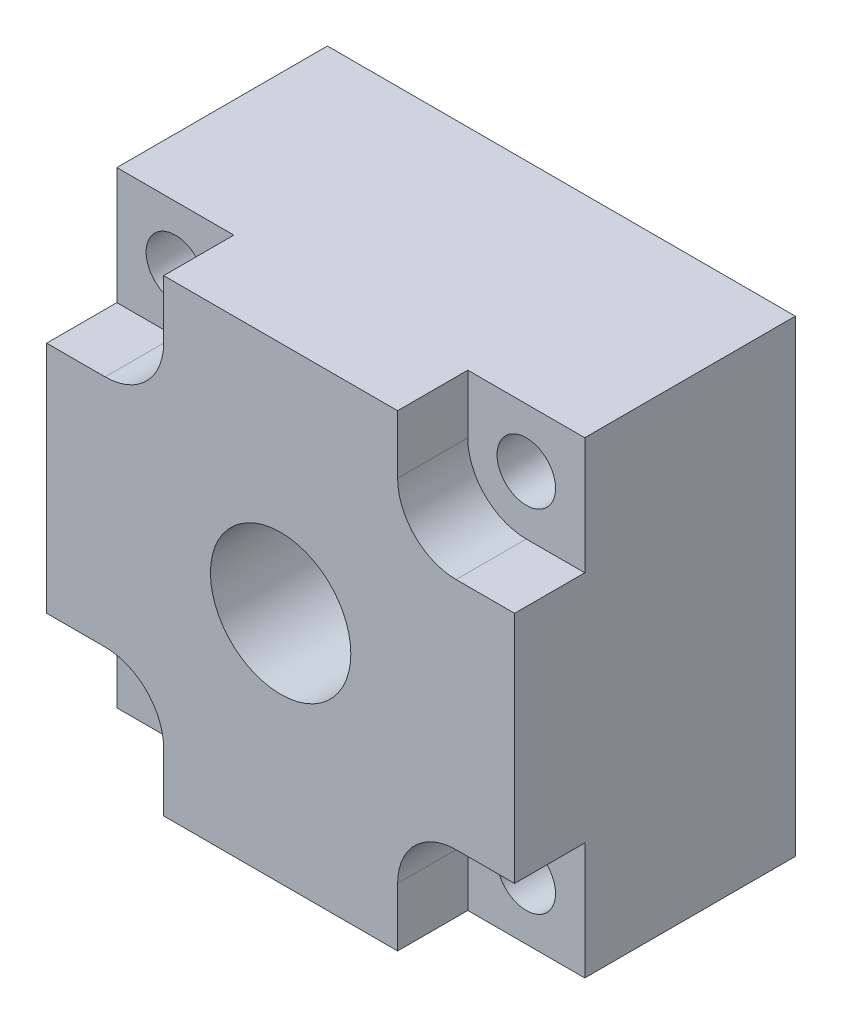
SolidWorks part; units mm, degrees
ref_plane "정면" through (0, 0, 0) normal (0, 0, 1) x (1, 0, 0)
ref_plane "윗면" through (0, 0, 0) normal (0, 1, 0) x (1, 0, 0)
ref_plane "우측면" through (0, 0, 0) normal (1, 0, 0) x (0, 0, -1)
sketch "스케치1" plane through (0, 0, 0) normal (0, 0, 1) x (1, 0, 0)
  line L1 (-10, 10) -> (10, 10)
  line L2 (-10, 10) -> (-10, -10)
  line L3 (-10, -10) -> (10, -10)
  line L4 (10, 10) -> (10, -10)
  line L5 (-10, 10) -> (10, -10) construction
  line L6 (-10, -10) -> (10, 10) construction
  line L7 (-7.5, 7.5) -> (7.5, 7.5) construction
  line L8 (-7.5, 7.5) -> (-7.5, -7.5) construction
  line L9 (-7.5, -7.5) -> (7.5, -7.5) construction
  line L10 (7.5, 7.5) -> (7.5, -7.5) construction
  line L11 (-7.5, 7.5) -> (7.5, -7.5) construction
  line L12 (-7.5, -7.5) -> (7.5, 7.5) construction
  circle A1 centre (-7.5, 7.5) radius 1.25
  circle A2 centre (7.5, 7.5) radius 1.25
  circle A3 centre (-7.5, -7.5) radius 1.25
  circle A4 centre (7.5, -7.5) radius 1.25
  circle A5 centre (0, 0) radius 3
  point P0 (0, 0)
  point P6 (0, 0)
  dimension "D5" = 2.5
  dimension "D6" = 6
  dimension "D1" = 20
  dimension "D2" = 20
  dimension "D3" = 15
  dimension "D4" = 15
extrude "보스-돌출1" add sketch "스케치1" along normal blind 12
sketch "스케치2" plane through (0, 0, 0) normal (0, 0, -1) x (-1, 0, 0)
  circle A0 centre (0, 0) radius 7.5
  dimension "D1" = 15
extrude "컷-돌출1" cut sketch "스케치2" against normal blind 5.2
sketch "스케치3" plane through (0, 0, 12) normal (0, 0, 1) x (1, 0, 0)
  line L0 (-10, -10) -> (-5, -10)
  line L2 (-7.5, -5) -> (-10, -5)
  line L4 (-5, -7.5) -> (-5, -10)
  line L6 (-10, -5) -> (-10, -10)
  line L9 (-7.5, 5) -> (-10, 5)
  line L10 (-5, 7.5) -> (-5, 10)
  line L11 (-5, 10) -> (-10, 10)
  line L12 (-10, 5) -> (-10, 10)
  line L15 (7.5, 5) -> (10, 5)
  line L16 (5, 7.5) -> (5, 10)
  line L17 (5, 10) -> (10, 10)
  line L18 (10, 5) -> (10, 10)
  line L21 (7.5, -5) -> (10, -5)
  line L22 (5, -7.5) -> (5, -10)
  line L23 (5, -10) -> (10, -10)
  line L24 (10, -5) -> (10, -10)
  arc A0 (-7.5, 5) -> (-5, 7.5) centre (-7.5, 7.5) ccw
  arc A1 (5, 7.5) -> (7.5, 5) centre (7.5, 7.5) ccw
  arc A2 (7.5, -5) -> (5, -7.5) centre (7.5, -7.5) ccw
  arc A3 (-5, -7.5) -> (-7.5, -5) centre (-7.5, -7.5) ccw
extrude "컷-돌출2" cut sketch "스케치3" against normal blind 3
